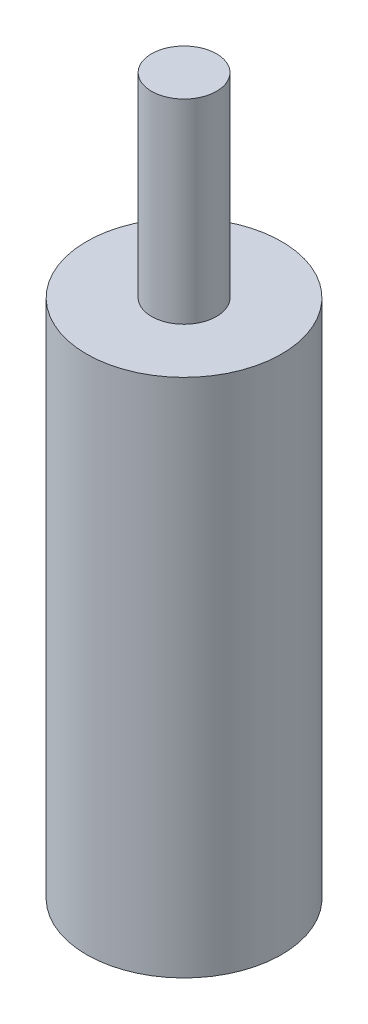
SolidWorks part; units mm, degrees
ref_plane "Front Plane" through (0, 0, 0) normal (0, 0, 1) x (1, 0, 0)
ref_plane "Top Plane" through (0, 0, 0) normal (0, 1, 0) x (1, 0, 0)
ref_plane "Right Plane" through (0, 0, 0) normal (1, 0, 0) x (0, 0, -1)
sketch "Sketch1" plane through (0, 0, 0) normal (0, 1, 0) x (1, 0, 0)
  circle A0 centre (0, 0) radius 4.7625
  dimension "D1" = 9.525
extrude "Boss-Extrude1" add sketch "Sketch1" along normal blind 25.4
sketch "Sketch2" plane through (0, 25.4, 0) normal (0, 1, 0) x (1, 0, 0)
  circle A0 centre (0, 0) radius 1.5875
  dimension "D1" = 3.175
extrude "Boss-Extrude2" add sketch "Sketch2" along normal blind 9.525
sketch "Sketch3" plane through (0, 0, 0) normal (0, -1, 0) x (1, 0, 0)
  circle A0 centre (0, 0) radius 1.5875
  dimension "D1" = 3.175
extrude "Cut-Extrude1" cut sketch "Sketch3" against normal blind 9.525
